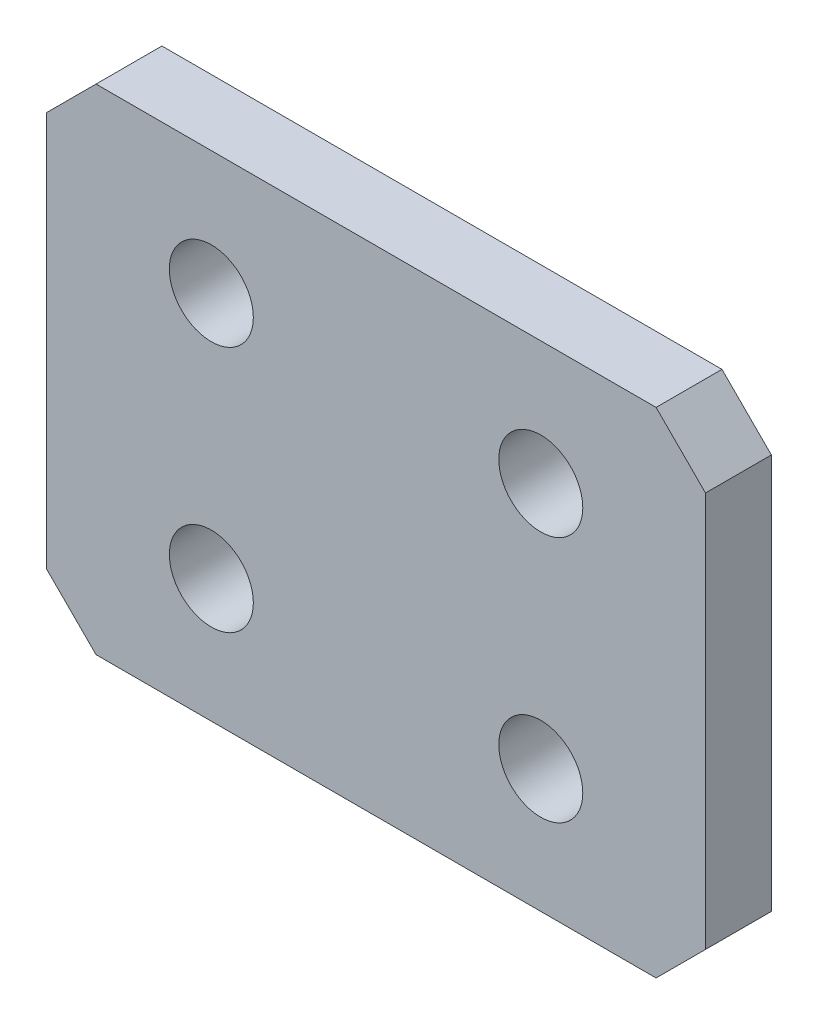
SolidWorks part; units mm, degrees
material "5052-O"
ref_plane "前基準面" through (0, 0, 0) normal (0, 0, 1) x (1, 0, 0)
ref_plane "上基準面" through (0, 0, 0) normal (0, 1, 0) x (1, 0, 0)
ref_plane "右基準面" through (0, 0, 0) normal (1, 0, 0) x (0, 0, -1)
sketch "Sketch1" plane through (0, 0, 0) normal (0, 0, 1) x (1, 0, 0)
  line L1 (-20, -15) -> (20, -15)
  line L2 (-20, -15) -> (-20, 15)
  line L3 (-20, 15) -> (20, 15)
  line L4 (20, -15) -> (20, 15)
  line L5 (-20, -15) -> (20, 15) construction
  line L6 (-20, 15) -> (20, -15) construction
  point P0 (0, 0)
  dimension "D1" = 30
  dimension "D2" = 40
extrude "Boss-Extrude1" add sketch "Sketch1" along normal blind 4
sketch "Sketch3" plane through (0, 0, 4) normal (0, 0, 1) x (1, 0, 0)
  line L0 (10, 7.5) -> (10, -7.5) construction
  line L1 (10, 0) -> (20, 0) construction
  line L2 (20, -15) -> (20, 15) construction
  circle A0 centre (10, 7.5) radius 2.55
  circle A1 centre (10, -7.5) radius 2.55
  dimension "D1" = 5.1
  dimension "D2" = 15
  dimension "D3" = 10
extrude "Cut-Extrude2" cut sketch "Sketch3" against normal through all
chamfer "Chamfer1" distance 3 angle 45 4 edges at (20, 15, 2) (-20, 15, 2) (20, -15, 2) (-20, -15, 2)
pattern_linear "LPattern1" count 2 spacing 20 along (-1, 0, 0) of "Cut-Extrude2"
